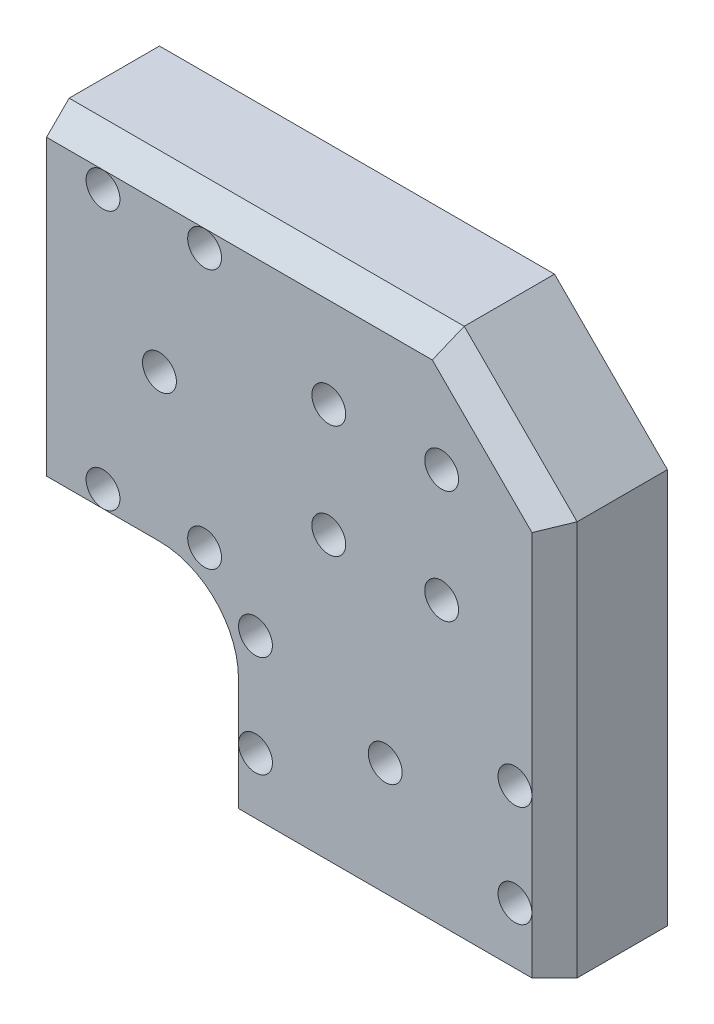
SolidWorks part; units mm, degrees
ref_plane "Front Plane" through (0, 0, 0) normal (0, 0, 1) x (1, 0, 0)
ref_plane "Top Plane" through (0, 0, 0) normal (0, 1, 0) x (1, 0, 0)
ref_plane "Right Plane" through (0, 0, 0) normal (1, 0, 0) x (0, 0, -1)
sketch "Sketch1" plane through (0, 0, 0) normal (0, 0, 1) x (1, 0, 0)
  line L0 (0, 0) -> (0, -30)
  line L1 (-5, -5) -> (5, -5)
  line L2 (-5, -5) -> (-5, 5)
  line L3 (-5, 5) -> (5, 5)
  line L4 (5, -5) -> (5, 5)
  line L5 (-5, -5) -> (5, 5) construction
  line L6 (-5, 5) -> (5, -5) construction
  line L7 (0, -30) -> (0, -10)
  line L8 (-15, -30) -> (15, -30)
  line L9 (-8, -30) -> (8, -30)
  line L10 (-8, -30) -> (8, -30)
  line L11 (-8, -30) -> (-8, -10)
  line L12 (8, -30) -> (8, -10)
  line L13 (-8, -10) -> (8, -10)
  line L14 (-15, -30) -> (15, -30)
  line L15 (-15, -30) -> (-15, 5)
  line L16 (15, -30) -> (15, 5)
  line L17 (-15, 5) -> (15, 5)
  line L18 (-30, 15) -> (5, 15)
  line L19 (-30, -15) -> (5, -15)
  line L20 (-30, 8) -> (-30, -8)
  line L21 (-30, 8) -> (-10, 8)
  line L22 (-10, 8) -> (-10, -8)
  line L23 (-30, -8) -> (-10, -8)
  line L24 (-30, 15) -> (-30, -15)
  line L25 (5, 15) -> (5, -15)
  line L26 (5, 15) -> (15, 5)
  circle A0 centre (-5, 5) radius 1.5
  circle A1 centre (5, 5) radius 1.5
  circle A2 centre (5, -5) radius 1.5
  circle A3 centre (-5, -5) radius 1.5
  point P0 (0, 0)
  point P15 (0, 0)
  point P20 (0, -30)
  point P23 (0, -30)
  point P38 (0, 0)
  dimension "D2" = 3
  dimension "D1" = 10
  dimension "D4" = 30
  dimension "D5" = 20
  dimension "D6" = 30
  dimension "D7" = 16
  dimension "D8" = 20
  dimension "D9" = 35
  dimension "D3" = 4
  dimension "D10" = 2
extrude "Boss-Extrude1" add sketch "Sketch1" along normal blind 10
sketch "Sketch2" plane through (0, -30, 0) normal (0, -1, 0) x (1, 0, 0)
  line L0 (0, 0) -> (0, -0.5)
  line L1 (-15, 0) -> (15, 0) construction
  circle A0 centre (0, -0.5) radius 8
  line M2 (-15, 0) -> (15, 0)
  dimension "D2" = 16
  dimension "D1" = 0.5
extrude "Cut-Extrude1" cut sketch "Sketch2" against normal blind 20 contours A0 M2
sketch "Sketch3" plane through (-30, 0, 0) normal (-1, 0, 0) x (0, 0, 1)
  line L0 (0, 0) -> (-0.5, 0)
  line L1 (0, 15) -> (0, -15) construction
  circle A0 centre (-0.5, 0) radius 8
  line M2 (0, 15) -> (0, -15)
  dimension "D2" = 16
  dimension "D1" = 0.5
extrude "Cut-Extrude2" cut sketch "Sketch3" against normal blind 20 contours A0 M2
sketch "Sketch4" plane through (0, 0, 0) normal (0, 0, -1) x (-1, 0, 0)
  line L0 (0, 0) -> (0, -30) construction
  line L1 (0, -30) -> (0, -10) construction
  line L2 (-15, -30) -> (-15, 5) construction
  line L3 (15, -30) -> (15, 5) construction
  line L4 (-5, -5) -> (5, -5)
  line L5 (-5, 5) -> (-5, -5)
  line L6 (5, 5) -> (-5, 5)
  line L7 (5, -5) -> (5, 5)
  line L8 (-5, -5) -> (5, -5)
  line L9 (-5, 5) -> (-5, -5)
  line L10 (5, 5) -> (-5, 5)
  line L11 (5, -5) -> (5, 5)
  line L12 (30, -8) -> (30, 8)
  line L13 (10, -8) -> (30, -8)
  line L14 (10, 8) -> (10, -8)
  line L15 (30, 8) -> (10, 8)
  line L16 (30, -8) -> (30, 8)
  line L17 (10, -8) -> (30, -8)
  line L18 (10, 8) -> (10, -8)
  line L19 (30, 8) -> (10, 8)
  line L20 (30, 15) -> (-5, 15)
  line L21 (30, -15) -> (30, 15)
  line L22 (-5, -15) -> (30, -15)
  line L23 (-5, 15) -> (-5, -15)
  line L24 (30, 15) -> (-5, 15)
  line L25 (30, -15) -> (30, 15)
  line L26 (-5, -15) -> (30, -15)
  line L27 (-5, 15) -> (-5, -15)
  line L28 (15, 5) -> (-15, 5) construction
  line L29 (-5, 15) -> (-15, 5) construction
  line L30 (8, -30) -> (-8, -30) construction
  line L31 (8, -30) -> (-8, -30) construction
  line L32 (8, -30) -> (8, -10) construction
  line L33 (8, -10) -> (-8, -10) construction
  line L34 (-8, -30) -> (-8, -10) construction
  line L35 (15, -30) -> (-15, -30) construction
  line L36 (15, -30) -> (-15, -30) construction
  line L37 (0, 0) -> (0, -30)
  line L38 (0, -30) -> (0, -10)
  line L39 (-15, -30) -> (-15, 5)
  line L40 (15, -30) -> (15, 5)
  line L41 (15, 5) -> (-15, 5)
  line L42 (-5, 15) -> (-15, 5)
  line L43 (8, -30) -> (-8, -30)
  line L44 (8, -30) -> (-8, -30)
  line L45 (8, -30) -> (8, -10)
  line L46 (8, -10) -> (-8, -10)
  line L47 (-8, -30) -> (-8, -10)
  line L48 (15, -30) -> (-15, -30)
  line L49 (15, -30) -> (-15, -30)
  circle A1 centre (5, -5) radius 1.5
  circle A2 centre (5, -5) radius 1.5
  circle A3 centre (-5, -5) radius 1.5
  circle A4 centre (-5, -5) radius 1.5
  circle A5 centre (-5, 5) radius 1.5
  circle A6 centre (-5, 5) radius 1.5
  circle A7 centre (5, 5) radius 1.5
  circle A8 centre (5, 5) radius 1.5
  arc M32 (3.5, 5) -> (6.5, 5) centre (5, 5) cw
  line M33 (6.5, 5) -> (3.5, 5)
  arc M34 (-6.5, 5) -> (-3.5, 5) centre (-5, 5) cw
  line M35 (-3.5, 5) -> (-6.5, 5)
  dimension "D1" = 0
  dimension "D2" = 0
  dimension "D3" = 0
  dimension "D4" = 0
  dimension "D5" = 0
  dimension "D6" = 0
  dimension "D7" = 0
extrude "Cut-Extrude3" cut sketch "Sketch4" against normal blind 20 contours M32 M33 | L11 A8 M33 | A8 L11 M33 | L8 A2 L11 | L11 A2 L8 | L27 M34 M35 | L27 M34 M35 | L9 A6 M35 | A6 L9 M35 | L27 A4 | L27 A4 L8 | L8 A4 L27
sketch "Sketch5" plane through (0, 0, 0) normal (0, 0, -1) x (-1, 0, 0)
  line L0 (30, 11.4922) -> (25, 11.4922)
  line L1 (30, 15) -> (30, 7.9844) construction
  line L2 (25, 11.4922) -> (16, 11.4922)
  line L3 (0, 0) -> (31.3676, 0)
  circle A0 centre (16, 11.4922) radius 1.5
  circle A1 centre (25, 11.4922) radius 1.5
  circle A2 centre (25, -11.4922) radius 1.5
  circle A3 centre (16, -11.4922) radius 1.5
  circle A4 centre (11.4922, -16) radius 1.5
  circle A5 centre (11.4922, -25) radius 1.5
  circle A6 centre (-11.4922, -16) radius 1.5
  circle A7 centre (-11.4922, -25) radius 1.5
  point P25 (0, 0)
  dimension "D3" = 3
  dimension "D1" = 5
  dimension "D2" = 9
  dimension "D4" = 2
extrude "Cut-Extrude4" cut sketch "Sketch5" against normal blind 20
fillet "Fillet1" radius 5 1 edges at (-15, -15, 5)
chamfer "Chamfer1" distance 2 angle 45 9 edges at (-25, -15, 0) (-25, -15, 10) (-15, -25, 10) (-15, -25, 0) (-16.4645, -16.4645, 0) (-16.4645, -16.4645, 10) (-12.5, 15, 10) (10, 10, 10) (15, -12.5, 10)
sketch "Sketch6" plane through (0, 0, 10) normal (0, 0, 1) x (1, 0, 0)
  line L0 (-30, 0) -> (-20, 0)
  line L1 (-30, 13) -> (-30, -13) construction
  circle A0 centre (-20, 0) radius 1.5
  circle A1 centre (0, -20) radius 1.5
  point P10 (0, 0)
  dimension "D2" = 3
  dimension "D1" = 10
  dimension "D3" = 2
extrude "Cut-Extrude5" cut sketch "Sketch6" against normal blind 20 contours A1 | A0
